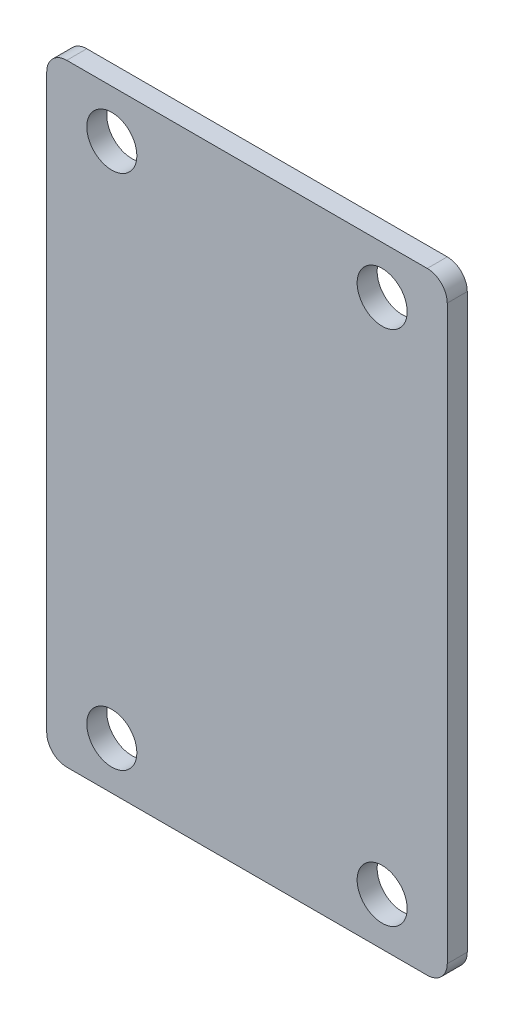
SolidWorks part; units mm, degrees
ref_plane "Front Plane" through (0, 0, 0) normal (0, 0, 1) x (1, 0, 0)
ref_plane "Top Plane" through (0, 0, 0) normal (0, 1, 0) x (1, 0, 0)
ref_plane "Right Plane" through (0, 0, 0) normal (1, 0, 0) x (0, 0, -1)
sketch "Sketch1" plane through (0, 0, 0) normal (0, 0, 1) x (1, 0, 0)
  line L0 (0, 14.2837) -> (0, 7.2467) construction
  line L1 (0, -7.2467) -> (0, -14.2837) construction
  line L2 (-1, -15.2837) -> (-19, -15.2837) construction
  line L3 (-20, -14.2837) -> (-20, -7.2467) construction
  line L4 (-20, 7.2467) -> (-20, 14.2837) construction
  line L5 (-19, 15.2837) -> (-1, 15.2837) construction
  line L6 (0, 14.2837) -> (0, -7.2467)
  line L7 (0, -7.2467) -> (0, -14.2837)
  line L8 (-1, -15.2837) -> (-19, -15.2837)
  line L9 (-20, -14.2837) -> (-20, -7.2467)
  line L10 (-20, -7.2467) -> (-20, 14.2837)
  line L11 (-19, 15.2837) -> (-1, 15.2837)
  arc A0 (0, 14.2837) -> (-1, 15.2837) centre (-1, 14.2837) ccw construction
  arc A1 (-1, -15.2837) -> (0, -14.2837) centre (-1, -14.2837) ccw construction
  arc A2 (-20, -14.2837) -> (-19, -15.2837) centre (-19, -14.2837) ccw construction
  arc A3 (-19, 15.2837) -> (-20, 14.2837) centre (-19, 14.2837) ccw construction
  arc A4 (0, 14.2837) -> (-1, 15.2837) centre (-1, 14.2837) ccw
  arc A5 (-1, -15.2837) -> (0, -14.2837) centre (-1, -14.2837) ccw
  arc A6 (-20, -14.2837) -> (-19, -15.2837) centre (-19, -14.2837) ccw
  arc A7 (-19, 15.2837) -> (-20, 14.2837) centre (-19, 14.2837) ccw
  circle A8 centre (-16.75, -12.908) radius 1.25 construction
  circle A9 centre (-3.25, -12.908) radius 1.25 construction
  circle A10 centre (-3.25, 12.908) radius 1.25 construction
  circle A11 centre (-16.75, 12.908) radius 1.25 construction
  circle A12 centre (-16.75, -12.908) radius 1.25
  circle A13 centre (-3.25, -12.908) radius 1.25
  circle A14 centre (-3.25, 12.908) radius 1.25
  circle A15 centre (-16.75, 12.908) radius 1.25
extrude "Boss-Extrude1" add sketch "Sketch1" along normal blind 1
